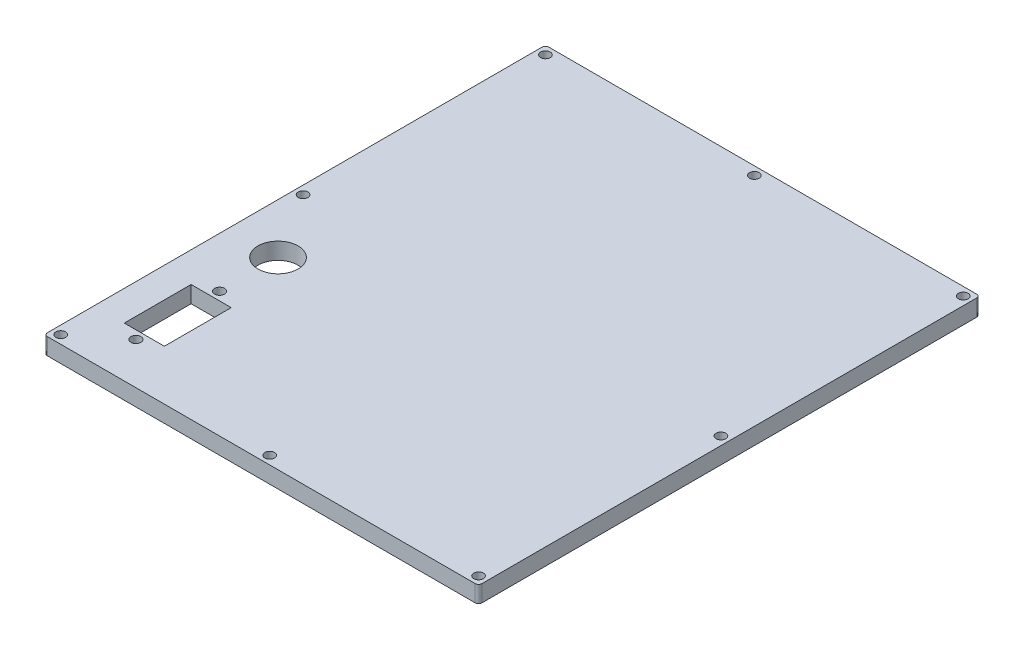
SolidWorks part; units mm, degrees
ref_plane "前视基准面" through (0, 0, 0) normal (0, 0, 1) x (1, 0, 0)
ref_plane "上视基准面" through (0, 0, 0) normal (0, 1, 0) x (1, 0, 0)
ref_plane "右视基准面" through (0, 0, 0) normal (1, 0, 0) x (0, 0, -1)
sketch "Sketch1" plane through (0, 0, 0) normal (0, 1, 0) x (1, 0, 0)
  line L0 (-65, 75) -> (65, 75)
  line L1 (-60, 70) -> (60, 70)
  line L2 (-60, 70) -> (-60, -70)
  line L3 (-60, -70) -> (60, -70)
  line L4 (60, 70) -> (60, -70)
  line L5 (-60, 70) -> (60, -70) construction
  line L6 (-60, -70) -> (60, 70) construction
  line L7 (65, 75) -> (65, -75)
  line L8 (-65, -75) -> (65, -75)
  line L9 (-65, 75) -> (-65, -75)
  point P0 (0, 0)
  dimension "D1" = 120
  dimension "D2" = 140
  dimension "D3" = 5
extrude "Boss-Extrude1" add sketch "Sketch1" along normal blind 140
sketch "Sketch2" plane through (0, 140, 0) normal (0, 1, 0) x (1, 0, 0)
  line L4 (-65, 75) -> (-65, -75)
  line L5 (-65, -75) -> (65, -75)
  line L6 (65, -75) -> (65, 75)
  line L7 (65, 75) -> (-65, 75)
  line L8 (-65, 75) -> (-65, -75)
  line L9 (-65, -75) -> (65, -75)
  line L10 (65, -75) -> (65, 75)
  line L11 (65, 75) -> (-65, 75)
  dimension "D1" = 0
extrude "Boss-Extrude2" add sketch "Sketch2" along normal blind 5
sketch "Sketch3" plane through (0, 0, 0) normal (0, -1, 0) x (1, 0, 0)
  line L0 (60, -70) -> (-60, -70) construction
  line L1 (60, 70) -> (60, -70) construction
  line L2 (-60, 70) -> (60, 70) construction
  line L3 (-60, -70) -> (-60, 70) construction
  line L4 (-65, 75) -> (-65, -75)
  line L5 (-65, -75) -> (65, -75)
  line L6 (65, -75) -> (65, 75)
  line L7 (65, 75) -> (-65, 75)
  line L8 (-65, 75) -> (-65, -75)
  line L9 (-65, -75) -> (65, -75)
  line L10 (65, -75) -> (65, 75)
  line L11 (65, 75) -> (-65, 75)
  line L12 (60, -70) -> (-60, -70)
  line L13 (60, 70) -> (60, -70)
  line L14 (-60, 70) -> (60, 70)
  line L15 (-60, -70) -> (-60, 70)
  line L16 (-62.5, 72.5) -> (62.5, 72.5)
  line L17 (62.5, 72.5) -> (62.5, -72.5)
  line L18 (62.5, -72.5) -> (-62.5, -72.5)
  line L19 (-62.5, -72.5) -> (-62.5, 72.5)
  circle A1 centre (0, 72.5) radius 1.45
  circle A2 centre (-62.5, 72.5) radius 1.45
  circle A3 centre (-62.5, -72.5) radius 1.45
  circle A4 centre (62.5, -72.5) radius 1.45
  circle A5 centre (62.5, 72.5) radius 1.45
  circle A6 centre (62.5, 0) radius 1.45
  circle A7 centre (-62.5, 0) radius 1.45
  circle A8 centre (0, -72.5) radius 1.45
  dimension "D2" = 2.5
  dimension "D1" = 0
extrude "Cut-Extrude1" cut sketch "Sketch3" against normal blind 12 contours L18 A8 | L18 A8 | L18 A4 L17 | L17 A4 L18 | L17 A6 | L17 A6 | L16 A5 L17 | L17 A5 L16 | L16 A1 | L16 A1 | L19 A2 L16 | L16 A2 L19 | L19 A7 | L19 A7 | L19 A3 L18 | L18 A3 L19
sketch "Sketch4" plane through (0, 145, 0) normal (0, 1, 0) x (1, 0, 0)
  line L4 (65, 75) -> (-65, 75)
  line L5 (-65, 75) -> (-65, -75)
  line L6 (-65, -75) -> (65, -75)
  line L7 (65, -75) -> (65, 75)
  line L8 (65, 75) -> (-65, 75)
  line L9 (-65, 75) -> (-65, -75)
  line L10 (-65, -75) -> (65, -75)
  line L11 (65, -75) -> (65, 75)
  dimension "D1" = 0
extrude "Cut-Extrude2" cut sketch "Sketch4" against normal blind 140
sketch "Sketch6" plane through (0, 0, 0) normal (0, -1, 0) x (1, 0, 0)
  line L0 (60, -70) -> (-60, -70) construction
  line L1 (60, 70) -> (60, -70) construction
  line L2 (-60, 70) -> (60, 70) construction
  line L3 (-60, -70) -> (-60, 70) construction
  line L4 (60, -70) -> (-60, -70)
  line L5 (60, 70) -> (60, -70)
  line L6 (-60, 70) -> (60, 70)
  line L7 (-60, -70) -> (-60, 70)
extrude "Boss-Extrude3" add sketch "Sketch6" against normal blind 5
fillet "Fillet1" radius 1 4 edges at (-65, 2.5, 75) (-65, 2.5, -75) (65, 2.5, -75) (65, 2.5, 75)
sketch "Sketch7" plane through (0, 0, 0) normal (0, -1, 0) x (1, 0, 0)
  line L0 (60, 70) -> (-60, 70)
  line L1 (-60, 70) -> (-60, -70)
  line L2 (-60, -70) -> (60, -70)
  line L3 (60, -70) -> (60, 70)
  line L4 (64, 75) -> (-64, 75)
  line L5 (-65, 74) -> (-65, -74)
  line L6 (-64, -75) -> (64, -75)
  line L7 (65, -74) -> (65, 74)
  line L8 (64, 75) -> (-64, 75)
  line L9 (-65, 74) -> (-65, -74)
  line L10 (-64, -75) -> (64, -75)
  line L11 (65, -74) -> (65, 74)
  line L12 (59, 69) -> (-59, 69)
  line L13 (-59, 69) -> (-59, -69)
  line L14 (-59, -69) -> (59, -69)
  line L15 (59, -69) -> (59, 69)
  arc A0 (-60, 70) -> (-60, 70) centre (-60, 70) ccw
  arc A1 (-60, -70) -> (-60, -70) centre (-60, -70) ccw
  arc A2 (60, -70) -> (60, -70) centre (60, -70) ccw
  arc A3 (60, 70) -> (60, 70) centre (60, 70) ccw
  arc A4 (-64, 75) -> (-65, 74) centre (-64, 74) ccw
  arc A5 (-65, -74) -> (-64, -75) centre (-64, -74) ccw
  arc A6 (64, -75) -> (65, -74) centre (64, -74) ccw
  arc A7 (65, 74) -> (64, 75) centre (64, 74) ccw
  arc A8 (-64, 75) -> (-65, 74) centre (-64, 74) ccw
  arc A9 (-65, -74) -> (-64, -75) centre (-64, -74) ccw
  arc A10 (64, -75) -> (65, -74) centre (64, -74) ccw
  arc A11 (65, 74) -> (64, 75) centre (64, 74) ccw
  arc A12 (-59, 69) -> (-59, 69) centre (-59, 69) ccw
  arc A13 (-59, -69) -> (-59, -69) centre (-59, -69) ccw
  arc A14 (59, -69) -> (59, -69) centre (59, -69) ccw
  arc A15 (59, 69) -> (59, 69) centre (59, 69) ccw
  dimension "D1" = 0
  dimension "D2" = 5
  dimension "D3" = 1
extrude "Cut-Extrude3" cut sketch "Sketch7" against normal blind 1 contours L2 L3 L0 L1 L15 L14 L13 L12
fillet "Fillet2" radius 1 8 edges at (-60, 0.5, 70) (-59, 0.5, 69) (-59, 0.5, -69) (-60, 0.5, -70) (60, 0.5, -70) (59, 0.5, -69) (60, 0.5, 70) (59, 0.5, 69)
sketch "Sketch8" plane through (0, 0, 0) normal (0, -1, 0) x (1, 0, 0)
  line L1 (-51, 62.5) -> (-49, 62.5)
  line L2 (-51, 62.5) -> (-51, 37.5)
  line L3 (-51, 37.5) -> (-49, 37.5)
  line L4 (-49, 62.5) -> (-49, 37.5)
  line L5 (-51, 62.5) -> (-49, 37.5) construction
  line L6 (-51, 37.5) -> (-49, 62.5) construction
  line L7 (-56, 60) -> (-44, 60)
  line L8 (-56, 60) -> (-56, 40)
  line L9 (-56, 40) -> (-44, 40)
  line L10 (-44, 60) -> (-44, 40)
  line L11 (-56, 60) -> (-44, 40) construction
  line L12 (-56, 40) -> (-44, 60) construction
  circle A0 centre (-50, 62.5) radius 1.5
  circle A1 centre (-50, 37.5) radius 1.5
  point P0 (-50, 50)
  point P7 (-50, 50)
  dimension "D3" = 12
  dimension "D1" = 2
  dimension "D2" = 25
  dimension "D4" = 20
extrude "Cut-Extrude4" cut sketch "Sketch8" against normal blind 10 contours L8 L9 L2 L7 | L2 L9 L4 L7 | L10 L7 L4 L9 | L4 A0 L2 L1 | L2 A0 L4 L1 | L4 A1 L2 L3 | L2 A1 L4 L3
sketch "Sketch9" plane through (0, 0, 0) normal (0, -1, 0) x (1, 0, 0)
  circle A0 centre (-50, 20) radius 6
extrude "Cut-Extrude5" cut sketch "Sketch9" against normal blind 10
